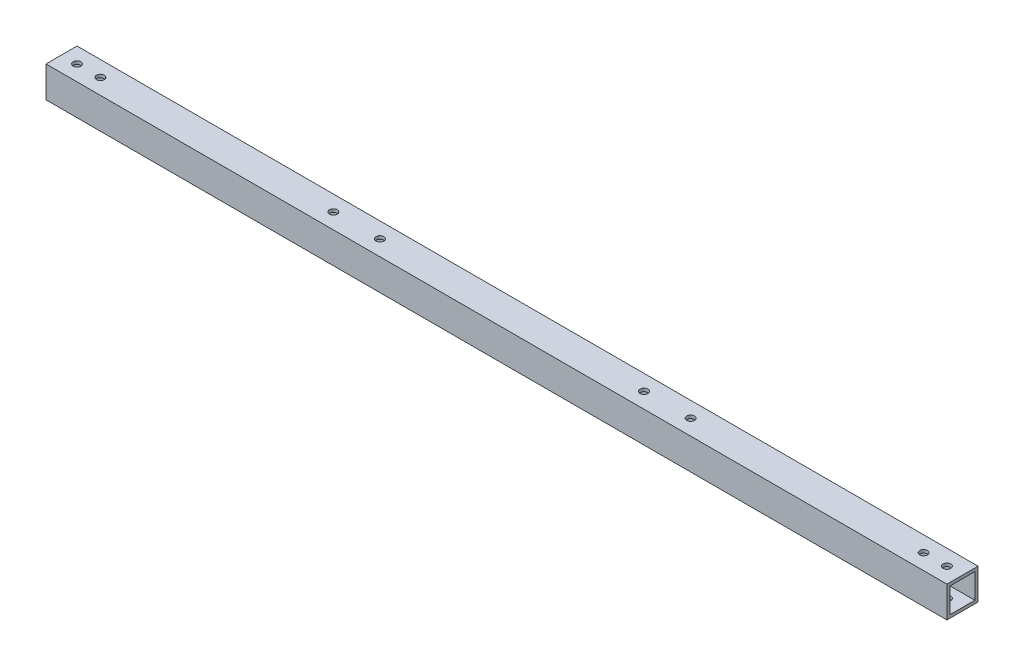
SolidWorks part; units mm, degrees
material "1345 Alloy"
ref_plane "Front Plane" through (0, 0, 0) normal (0, 0, 1) x (1, 0, 0)
ref_plane "Top Plane" through (0, 0, 0) normal (0, 1, 0) x (1, 0, 0)
ref_plane "Right Plane" through (0, 0, 0) normal (1, 0, 0) x (0, 0, -1)
sketch "Sketch1" plane through (0, 0, 0) normal (1, 0, 0) x (0, 0, -1)
  line L1 (-10, 10) -> (10, 10)
  line L2 (-10, 10) -> (-10, -10)
  line L3 (-10, -10) -> (10, -10)
  line L4 (10, 10) -> (10, -10)
  line L5 (-10, 10) -> (10, -10) construction
  line L6 (-10, -10) -> (10, 10) construction
  line L7 (-8, 8) -> (8, 8)
  line L8 (-8, 8) -> (-8, -8)
  line L9 (-8, -8) -> (8, -8)
  line L10 (8, 8) -> (8, -8)
  line L11 (-8, 8) -> (8, -8) construction
  line L12 (-8, -8) -> (8, 8) construction
  point P0 (0, 0)
  point P6 (0, 0)
  dimension "D1" = 20
  dimension "D2" = 20
  dimension "D3" = 16
  dimension "D4" = 16
extrude "Boss-Extrude1" add sketch "Sketch1" along normal blind 580
sketch "Sketch2" plane through (0, 10, 0) normal (0, 1, 0) x (1, 0, 0)
  line L0 (-16.9319, 0) -> (495.2657, 0) construction
  line L1 (580, 10) -> (580, -10) construction
  line L2 (0, 10) -> (0, -10) construction
  line L3 (10, 31.8777) -> (10, -17.8515) construction
  line L4 (570, 25.7534) -> (570, -31.8149) construction
  circle A0 centre (10, 0) radius 2.5
  circle A1 centre (570, 0) radius 2.5
  circle A3 centre (25, 0) radius 2.5
  circle A4 centre (555, 0) radius 2.5
  dimension "D1" = 5
  dimension "D2" = 5
  dimension "D7" = 15
  dimension "D3" = 10
  dimension "D4" = 10
  dimension "D8" = 15
  dimension "D5" = 2
  dimension "D6" = 2
extrude "Cut-Extrude1" cut sketch "Sketch2" against normal through all
sketch "Sketch3" plane through (0, 10, 0) normal (0, 1, 0) x (1, 0, 0)
  line L0 (290, 10) -> (290, -82.7489) construction
  line L1 (580, 10) -> (0, 10) construction
  line L2 (-51.465, 0) -> (614.1502, 0) construction
  line L3 (0, 10) -> (0, -10) construction
  line L4 (190, 28.9336) -> (190, -25.8549) construction
  circle A0 centre (175, 0) radius 2.5
  circle A1 centre (405, 0) radius 2.5
  circle A2 centre (205, 0) radius 2.5
  circle A3 centre (375, 0) radius 2.5
  dimension "D1" = 5
  dimension "D2" = 175
  dimension "D3" = 15
extrude "Cut-Extrude2" cut sketch "Sketch3" against normal through all
